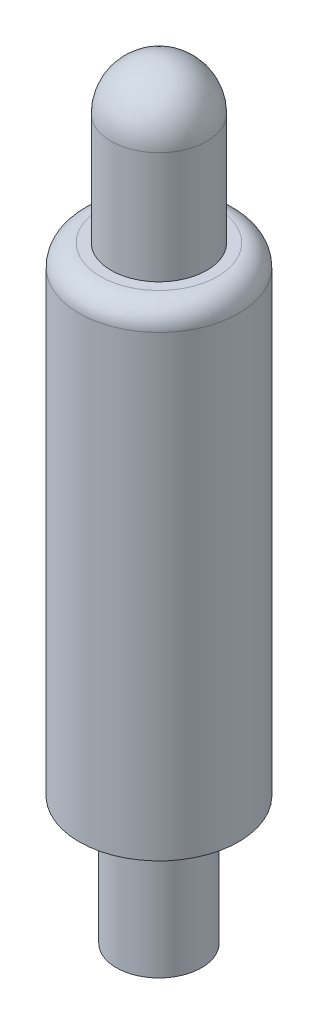
SolidWorks part; units mm, degrees
ref_plane "前视基准面" through (0, 0, 0) normal (0, 0, 1) x (1, 0, 0)
ref_plane "上视基准面" through (0, 0, 0) normal (0, 1, 0) x (1, 0, 0)
ref_plane "右视基准面" through (0, 0, 0) normal (1, 0, 0) x (0, 0, -1)
other "Configuration Table"
sketch "草图1" plane through (0, 0, 0) normal (0, 1, 0) x (1, 0, 0)
  circle A0 centre (0, 0) radius 0.75
  dimension "D1" = 1.5
extrude "凸台-拉伸1" add sketch "草图1" along normal blind 4.5
sketch "草图2" plane through (0, 4.5, 0) normal (0, 1, 0) x (1, 0, 0)
  circle A0 centre (0, 0) radius 0.45
  dimension "D1" = 0.9
extrude "凸台-拉伸2" add sketch "草图2" along normal blind 1.5 contours A0
sketch "草图3" plane through (0, 0, 0) normal (0, -1, 0) x (1, 0, 0)
  circle A0 centre (0, 0) radius 0.4
  dimension "D1" = 0.8
extrude "凸台-拉伸3" add sketch "草图3" along normal blind 1.2
fillet "圆角1" radius 0.2 1 edges at (0, 4.5, 0.75)
fillet "圆角2" radius 0.45 1 edges at (0, 6, 0.45)
